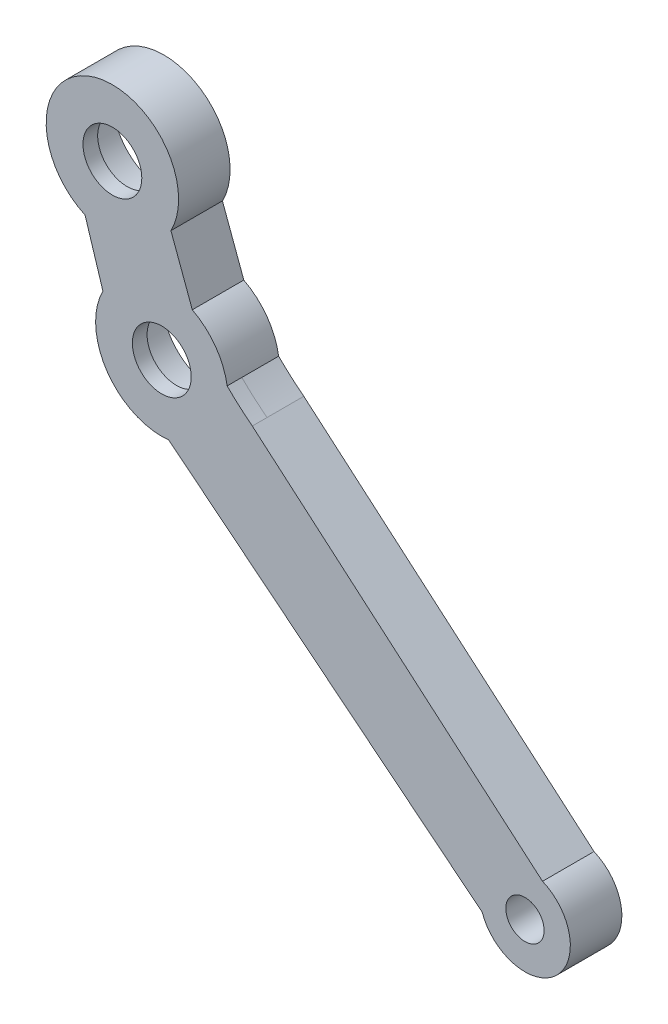
SolidWorks part; units mm, degrees
ref_plane "Front Plane" through (0, 0, 0) normal (0, 0, 1) x (1, 0, 0)
ref_plane "Top Plane" through (0, 0, 0) normal (0, 1, 0) x (1, 0, 0)
ref_plane "Right Plane" through (0, 0, 0) normal (1, 0, 0) x (0, 0, -1)
sketch "Sketch1" plane through (0, 0, 0) normal (0, 0, 1) x (1, 0, 0)
  line L4 (-169.858, 12.3281) -> (-127.2538, -21.9374)
  line L5 (-172.0822, 43.962) -> (-172.1127, 44.0448)
  line L6 (-177.675, 21.8061) -> (-177.6506, 21.7282)
  line L8 (-173.7115, 15.4274) -> (-172.7465, 14.6513)
  line L9 (-119.0478, -14.2184) -> (-158.4917, 19.6461)
  line L10 (-166.6455, 29.2483) -> (-169.5513, 37.1125)
  line L11 (-181.2224, 33.1197) -> (-178.7943, 25.3758)
  circle A2 centre (-170.7943, 21.2709) radius 6.9015
  arc A3 (-161.91, 22.6565) -> (-166.6455, 29.2483) centre (-170.7943, 21.2709) ccw
  arc A4 (-127.2538, -21.9374) -> (-119.0478, -14.2184) centre (-121.4321, -19.905) ccw
  arc A6 (-178.7943, 25.3758) -> (-169.858, 12.3281) centre (-170.7943, 21.2709) ccw
  circle A7 centre (-177.5085, 41.3176) radius 6.9
  arc A8 (-169.5513, 37.1125) -> (-181.2224, 33.1197) centre (-177.5085, 41.3176) ccw
  circle A9 centre (-121.4321, -19.905) radius 2.6
  parabola Q5 (-158.4917, 19.6461) -> (-161.91, 22.6565) focus (-150.532, 35.2115) apex (-163.1218, 23.941)
extrude "Boss-Extrude1" add sketch "Sketch1" along normal blind 5 contours L9 Q5 A3 L10 A8 L11 A6 L4 A4 A2 A7 A9
sketch "Sketch2" plane through (0, 0, 5) normal (0, 0, 1) x (1, 0, 0)
  line L4 (-119.0478, -14.2184) -> (-158.4917, 19.6461)
  line L5 (-166.6455, 29.2483) -> (-169.5513, 37.1125)
  line L6 (-181.2224, 33.1197) -> (-178.7943, 25.3758)
  line L7 (-169.858, 12.3281) -> (-127.2538, -21.9374)
  line L8 (-119.0478, -14.2184) -> (-158.4917, 19.6461)
  line L9 (-166.6455, 29.2483) -> (-169.5513, 37.1125)
  line L10 (-181.2224, 33.1197) -> (-178.7943, 25.3758)
  line L11 (-169.858, 12.3281) -> (-127.2538, -21.9374)
  circle A0 centre (-177.5085, 41.3176) radius 4
  circle A1 centre (-170.7943, 21.2709) radius 4
  circle A2 centre (-121.4321, -19.905) radius 2.6
  arc A4 (-161.91, 22.6565) -> (-166.6455, 29.2483) centre (-170.7943, 21.2709) ccw
  arc A5 (-169.5513, 37.1125) -> (-181.2224, 33.1197) centre (-177.5085, 41.3176) ccw
  arc A6 (-178.7943, 25.3758) -> (-169.858, 12.3281) centre (-170.7943, 21.2709) ccw
  arc A7 (-127.2538, -21.9374) -> (-119.0478, -14.2184) centre (-121.4321, -19.905) ccw
  arc A8 (-161.91, 22.6565) -> (-166.6455, 29.2483) centre (-170.7943, 21.2709) ccw
  arc A9 (-169.5513, 37.1125) -> (-181.2224, 33.1197) centre (-177.5085, 41.3176) ccw
  arc A10 (-178.7943, 25.3758) -> (-169.858, 12.3281) centre (-170.7943, 21.2709) ccw
  arc A11 (-127.2538, -21.9374) -> (-119.0478, -14.2184) centre (-121.4321, -19.905) ccw
  parabola Q1 (-158.4917, 19.6461) -> (-161.91, 22.6565) focus (-150.532, 35.2115) apex (-163.1218, 23.941)
  parabola Q2 (-158.4917, 19.6461) -> (-161.91, 22.6565) focus (-150.532, 35.2115) apex (-163.1218, 23.941)
  dimension "D2" = 8
  dimension "D3" = 8
  dimension "D1" = 0
extrude "Boss-Extrude2" add sketch "Sketch2" along normal blind 2
scale "Scale1" scale about centroid uniform scaling yes scale factor 1.5
